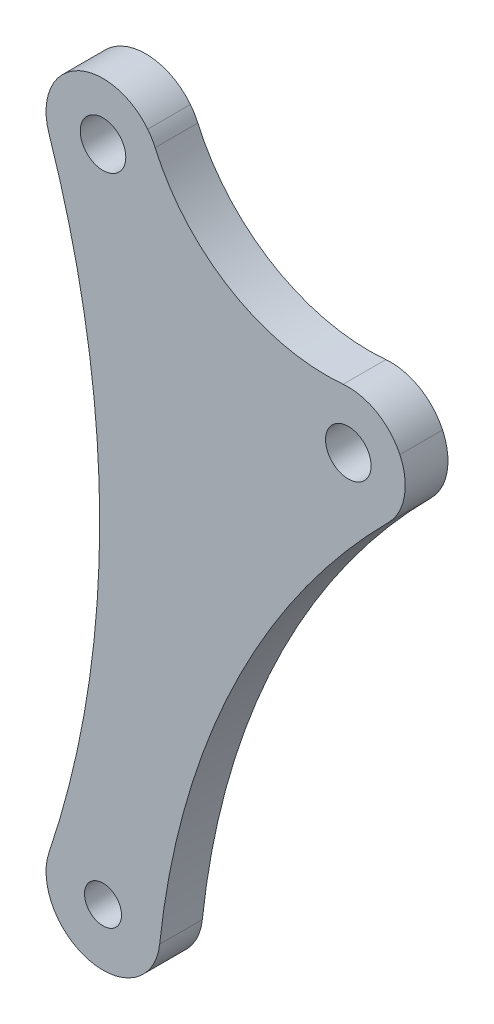
SolidWorks part; units mm, degrees
ref_plane "前视基准面" through (0, 0, 0) normal (0, 0, 1) x (1, 0, 0)
ref_plane "上视基准面" through (0, 0, 0) normal (0, 1, 0) x (1, 0, 0)
ref_plane "右视基准面" through (0, 0, 0) normal (1, 0, 0) x (0, 0, -1)
ref_plane "基准面4" through (0, 0, 0) normal (0, 0, -1) x (-1, 0, 0)
sketch "草图1" plane through (0, 0, 0) normal (0, 0, -1) x (-1, 0, 0)
  line L0 (3.3111, 16.0217) -> (3.3131, 16.0217)
  line L1 (3.295, 15.9735) -> (3.3111, 16.0217)
  arc A0 (3.3131, 16.0217) -> (-3.6194, 19.7723) centre (-0.4812, 17.2907) ccw
  arc A1 (-3.6194, 19.7723) -> (-4.1407, 18.9076) centre (-0.4812, 17.2907) ccw
  arc A2 (-4.1407, 18.9076) -> (-17.3517, 11.1206) centre (-16.1693, 24.2145) cw
  arc A3 (-17.3517, 11.1206) -> (-21.3337, 8.8326) centre (-17.709, 7.1333) ccw
  arc A4 (-21.3337, 8.8326) -> (-20.5427, 4.3096) centre (-17.7099, 7.1357) ccw
  arc A5 (-20.5427, 4.3096) -> (-4.4597, -29.3874) centre (-60.2315, -35.3197) cw
  arc A6 (-4.4597, -29.3874) -> (-1.8337, -32.7264) centre (-0.4826, -28.9616) ccw
  arc A7 (-1.8337, -32.7264) -> (2.3153, -31.8234) centre (-0.4798, -28.9642) ccw
  arc A8 (2.3153, -31.8234) -> (3.3133, -27.6934) centre (-0.4834, -28.9615) ccw
  arc A9 (3.3133, -27.6934) -> (3.295, 15.9735) centre (68.6418, -5.8326) cw
  circle A10 centre (-17.7114, 7.1362) radius 1.35
  circle A11 centre (-0.4809, -28.9628) radius 1.3
  circle A12 centre (-0.4809, 17.2912) radius 1.3
extrude "凸台-拉伸1" add sketch "草图1" against normal blind 3
sketch "草图2" plane through (0, 0, 3) normal (0, 0, 1) x (1, 0, 0)
  circle A0 centre (0.4809, 17.2912) radius 1.6
  circle A1 centre (17.7114, 7.1362) radius 1.6
  dimension "D1" = 3.2
extrude "切除-拉伸1" cut sketch "草图2" against normal through all
